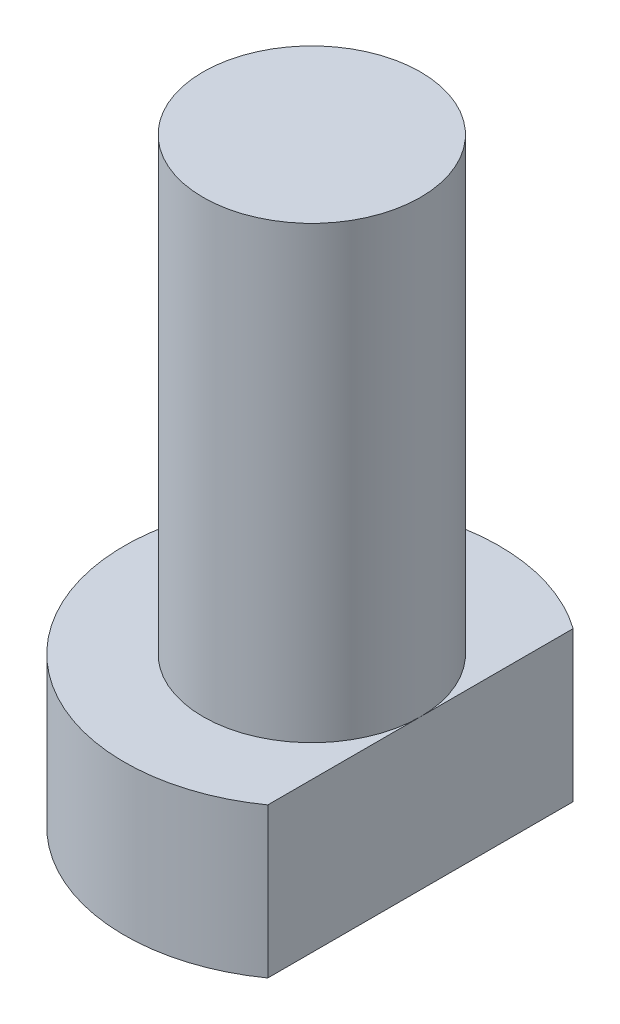
SolidWorks part; units mm, degrees
ref_plane "Front Plane" through (0, 0, 0) normal (0, 0, 1) x (1, 0, 0)
ref_plane "Top Plane" through (0, 0, 0) normal (0, 1, 0) x (1, 0, 0)
ref_plane "Right Plane" through (0, 0, 0) normal (1, 0, 0) x (0, 0, -1)
sketch "Sketch1" plane through (0, 0, 0) normal (0, 1, 0) x (1, 0, 0)
  circle A0 centre (0, 0) radius 2.5
  dimension "D1" = 5
extrude "Boss-Extrude1" add sketch "Sketch1" along normal blind 2
sketch "Sketch2" plane through (0, 2, 0) normal (0, 1, 0) x (1, 0, 0)
  circle A0 centre (0, 0) radius 1.45
extrude "Boss-Extrude2" add sketch "Sketch2" along normal blind 6
sketch "Sketch3" plane through (0, 2, 0) normal (0, 1, 0) x (1, 0, 0)
  line L0 (1.45, 2.0365) -> (1.45, -2.0365)
  circle A2 centre (0, 0) radius 2.5 construction
  arc A3 (1.45, -2.0365) -> (1.45, 2.0365) centre (0, 0) ccw
  point P3 (1.45, 0)
extrude "Cut-Extrude1" cut sketch "Sketch3" against normal blind 6
